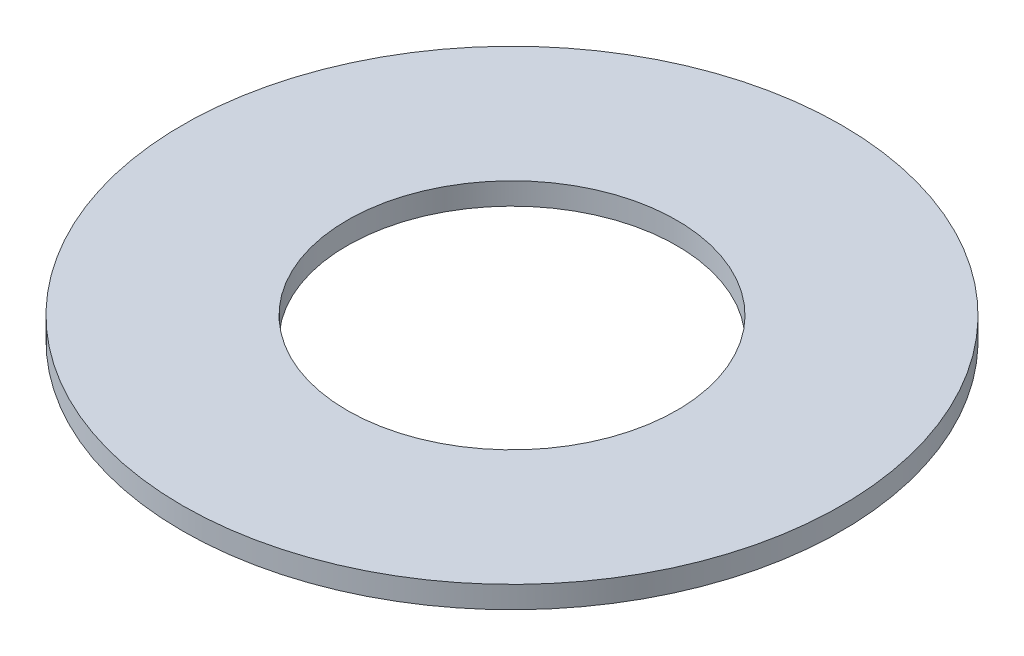
SolidWorks part; units mm, degrees
ref_plane "Front Plane" through (0, 0, 0) normal (0, 0, 1) x (1, 0, 0)
ref_plane "Top Plane" through (0, 0, 0) normal (0, 1, 0) x (1, 0, 0)
ref_plane "Right Plane" through (0, 0, 0) normal (1, 0, 0) x (0, 0, -1)
sketch "Sketch2" plane through (0, 0, 0) normal (0, 1, 0) x (1, 0, 0)
  circle A0 centre (0, 0) radius 9.525
  circle A1 centre (0, 0) radius 19.05
  dimension "D1" = 38.1
  dimension "D2" = 19.05
extrude "Boss-Extrude1" add sketch "Sketch2" along normal blind 1.27
